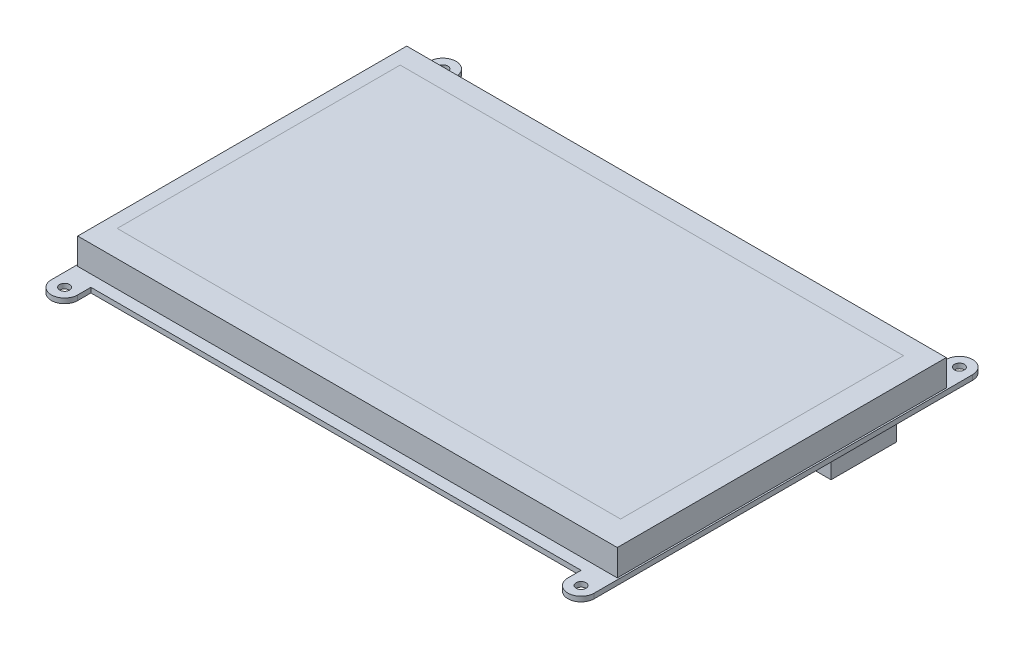
SolidWorks part; units mm, degrees
ref_plane "Front" through (0, 0, 0) normal (0, 0, 1) x (1, 0, 0)
ref_plane "Top" through (0, 0, 0) normal (0, 1, 0) x (1, 0, 0)
ref_plane "Right" through (0, 0, 0) normal (1, 0, 0) x (0, 0, -1)
sketch "Sketch1" plane through (0, 0, 0) normal (0, 1, 0) x (1, 0, 0)
  line L0 (0, 0) -> (12.9315, 0) construction
  line L1 (-74.5, -53.5) -> (74.5, -53.5)
  line L2 (-82.5, -23.8776) -> (-82.5, 23.8776)
  line L3 (-74.5, 53.5) -> (74.5, 53.5)
  line L4 (82.5, -23.8776) -> (82.5, 23.8776)
  line L5 (-82.5, -23.8776) -> (82.5, 23.8776) construction
  line L6 (-82.5, 23.8776) -> (82.5, -23.8776) construction
  line L7 (0, 0) -> (0, 10.1701) construction
  line L8 (82.5, 23.8776) -> (82.5, 57.5)
  line L9 (74.5, 57.5) -> (74.5, 53.5)
  line L10 (-74.5, 57.5) -> (-74.5, 53.5)
  line L11 (-82.5, 23.8776) -> (-82.5, 57.5)
  line L12 (74.5, -57.5) -> (74.5, -53.5)
  line L13 (82.5, -23.8776) -> (82.5, -57.5)
  line L14 (-82.5, -23.8776) -> (-82.5, -57.5)
  line L15 (-74.5, -57.5) -> (-74.5, -53.5)
  circle A0 centre (78.5, 57.5) radius 1.5
  arc A1 (82.5, 57.5) -> (74.5, 57.5) centre (78.5, 57.5) ccw
  arc A2 (-82.5, 57.5) -> (-74.5, 57.5) centre (-78.5, 57.5) cw
  circle A3 centre (-78.5, 57.5) radius 1.5
  arc A4 (82.5, -57.5) -> (74.5, -57.5) centre (78.5, -57.5) cw
  circle A5 centre (78.5, -57.5) radius 1.5
  circle A6 centre (-78.5, -57.5) radius 1.5
  arc A7 (-82.5, -57.5) -> (-74.5, -57.5) centre (-78.5, -57.5) ccw
  point P0 (0, 0)
  dimension "D1" = 3
  dimension "D2" = 112
  dimension "D3" = 154
  dimension "D4" = 2.5
  dimension "D6" = 2.5
  dimension "D5" = 107
  dimension "D7" = 8
extrude "Boss-Extrude1" add sketch "Sketch1" along normal blind 1.5
sketch "Sketch2" plane through (0, 0, 0) normal (0, -1, 0) x (1, 0, 0)
  line L1 (70.6742, -17.8025) -> (79.1702, -17.8025)
  line L2 (70.6742, -17.8025) -> (70.6742, -37.6392)
  line L3 (70.6742, -37.6392) -> (79.1702, -37.6392)
  line L4 (79.1702, -17.8025) -> (79.1702, -37.6392)
  line L5 (70.6742, -17.8025) -> (79.1702, -37.6392) construction
  line L6 (70.6742, -37.6392) -> (79.1702, -17.8025) construction
  line L7 (-18.5141, -5.9976) -> (0, -5.9976)
  line L8 (-18.5141, -5.9976) -> (-18.5141, -15.8759)
  line L9 (-18.5141, -15.8759) -> (0, -15.8759)
  line L10 (0, -5.9976) -> (0, -15.8759)
  line L11 (-18.5141, -5.9976) -> (0, -15.8759) construction
  line L12 (-18.5141, -15.8759) -> (0, -5.9976) construction
  point P0 (74.9222, -27.7209)
  point P5 (-9.2571, -10.9367)
extrude "Boss-Extrude2" add sketch "Sketch2" along normal blind 8
sketch "Sketch3" plane through (0, 1.5, 0) normal (0, 1, 0) x (1, 0, 0)
  line L0 (82.5, -57.5) -> (82.5, 57.5) construction
  line L1 (-82, -50) -> (82, -50)
  line L2 (-82, -50) -> (-82, 50)
  line L3 (-82, 50) -> (82, 50)
  line L4 (82, -50) -> (82, 50)
  line L5 (-82, -50) -> (82, 50) construction
  line L6 (-82, 50) -> (82, -50) construction
  point P0 (0, 0)
  dimension "D1" = 0.5
  dimension "D2" = 100
extrude "Boss-Extrude3" add sketch "Sketch3" along normal blind 8
sketch "Sketch4" plane through (0, 9.5, 0) normal (0, 1, 0) x (1, 0, 0)
  line L0 (82, 50) -> (-82, 50) construction
  line L1 (-78, 44) -> (75, 44)
  line L2 (-78, 44) -> (-78, -42)
  line L3 (-78, -42) -> (75, -42)
  line L4 (75, 44) -> (75, -42)
  line L5 (-82, -50) -> (82, -50) construction
  line L6 (82, -50) -> (82, 50) construction
  line L7 (-82, 50) -> (-82, -50) construction
  dimension "D1" = 6
  dimension "D2" = 8
  dimension "D3" = 7
  dimension "D4" = 4
split line "Split Line1"
sketch "Sketch5" plane through (0, 9.5, 0) normal (0, 1, 0) x (1, 0, 0)
  text T0 "Front\r\nTouchscreen" font "Century Gothic" height in points 50
extrude "Cut-Extrude1" [suppressed] cut sketch "Sketch5" against normal blind 1
sketch "Sketch6" plane through (0, 9.5, 0) normal (0, 1, 0) x (1, 0, 0)
  line L0 (-65, 30) -> (-35, 30) construction
  line L1 (-65, 38) -> (-35, 38)
  line L2 (-65, 22) -> (-35, 22)
  line L3 (-50, 0) -> (50, 0) construction
  line L4 (-50, 30) -> (-50, 10) construction
  line L5 (-50, 20) -> (-35, 20) construction
  line L6 (-65, 10) -> (-35, 10) construction
  line L7 (-65, 2) -> (-35, 2)
  line L8 (-65, 18) -> (-35, 18)
  line L9 (0, 0) -> (-158.4334, 0) construction
  line L10 (-65, -30) -> (-35, -30) construction
  line L11 (-65, -38) -> (-35, -38)
  line L12 (-65, -22) -> (-35, -22)
  line L13 (-65, -10) -> (-35, -10) construction
  line L14 (-65, -2) -> (-35, -2)
  line L15 (-65, -18) -> (-35, -18)
  line L16 (75, -42) -> (75, 44) construction
  line L17 (-14.4886, 0) -> (25.5114, 0)
  line L18 (-14.4886, 0) -> (-14.4886, -37)
  line L19 (-14.4886, -37) -> (25.5114, -37)
  line L20 (25.5114, 0) -> (25.5114, -37)
  line L21 (34, 39) -> (49, 39)
  line L22 (34, 39) -> (34, -37)
  line L23 (34, -37) -> (49, -37)
  line L24 (49, 39) -> (49, -37)
  line L25 (54, 39) -> (69, 39)
  line L26 (54, 39) -> (54, -37)
  line L27 (54, -37) -> (69, -37)
  line L28 (69, 39) -> (69, -37)
  line L29 (75, 44) -> (-78, 44) construction
  line L30 (-78, -42) -> (75, -42) construction
  arc A0 (-65, 38) -> (-65, 22) centre (-65, 30) ccw
  arc A1 (-35, 22) -> (-35, 38) centre (-35, 30) ccw
  arc A2 (-65, 2) -> (-65, 18) centre (-65, 10) cw
  arc A3 (-35, 18) -> (-35, 2) centre (-35, 10) cw
  arc A4 (-65, -38) -> (-65, -22) centre (-65, -30) cw
  arc A5 (-35, -22) -> (-35, -38) centre (-35, -30) cw
  arc A6 (-65, -2) -> (-65, -18) centre (-65, -10) ccw
  arc A7 (-35, -18) -> (-35, -2) centre (-35, -10) ccw
  point P2 (-50, 30)
  point P17 (-50, 10)
  point P26 (-50, -30)
  point P33 (-50, -10)
  dimension "D1" = 30
  dimension "D2" = 16
  dimension "D3" = 30
  dimension "D4" = 50
  dimension "D5" = 4
  dimension "D6" = 4
  dimension "D7" = 5
  dimension "D8" = 6
  dimension "D9" = 5
  dimension "D10" = 5
  dimension "D11" = 40
  dimension "D12" = 15
extrude "Cut-Extrude2" [suppressed] cut sketch "Sketch6" against normal blind 1
sketch "Sketch7" [suppressed] plane through (0, 8.5, 0) normal (0, 1, 0) x (1, 0, 0)
  line L0 (34, -5.244) -> (49, -5.244)
  line L1 (34, 39) -> (34, -37) construction
  line L2 (49, -37) -> (49, 39) construction
split line "Split Line2" [suppressed]
